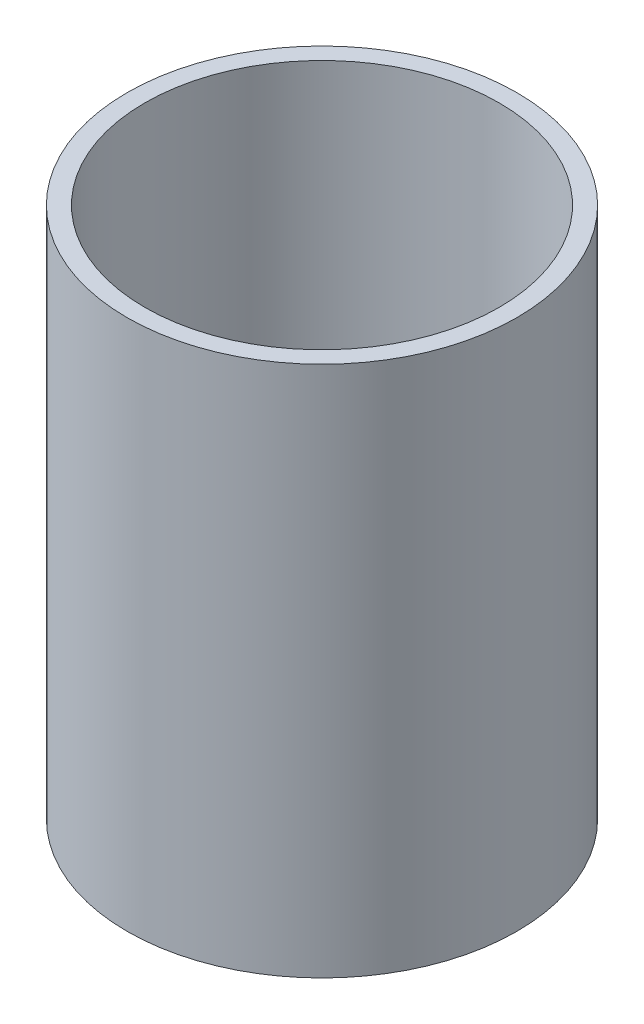
SolidWorks part; units mm, degrees
material "镍"
ref_plane "前视基准面" through (0, 0, 0) normal (0, 0, 1) x (1, 0, 0)
ref_plane "上视基准面" through (0, 0, 0) normal (0, 1, 0) x (1, 0, 0)
ref_plane "右视基准面" through (0, 0, 0) normal (1, 0, 0) x (0, 0, -1)
sketch "草图1" plane through (0, 0, 0) normal (0, 1, 0) x (1, 0, 0)
  circle A0 centre (0, 0) radius 55
  dimension "D1" = 110
extrude "拉伸1" add sketch "草图1" along normal blind 150
sketch "草图2" plane through (0, 150, 0) normal (0, 1, 0) x (-1, 0, 0)
  circle A0 centre (0, 0) radius 50
  dimension "D1" = 100
extrude "切除-拉伸1" cut sketch "草图2" against normal blind 145
sketch "草图3" plane through (0, 0, 0) normal (0, -1, 0) x (1, 0, 0)
  circle A0 centre (0, 0) radius 13.75
  dimension "D1" = 27.5
extrude "切除-拉伸2" cut sketch "草图3" against normal through all
equation "\"D1@切除-拉伸1\" = \"D1@拉伸1\" - 5"
equation "\"D1@草图1\" = \"D1@草图2\" + 10"
equation "\"D1@草图3\" = \"D1@草图1\" / 4.0"
